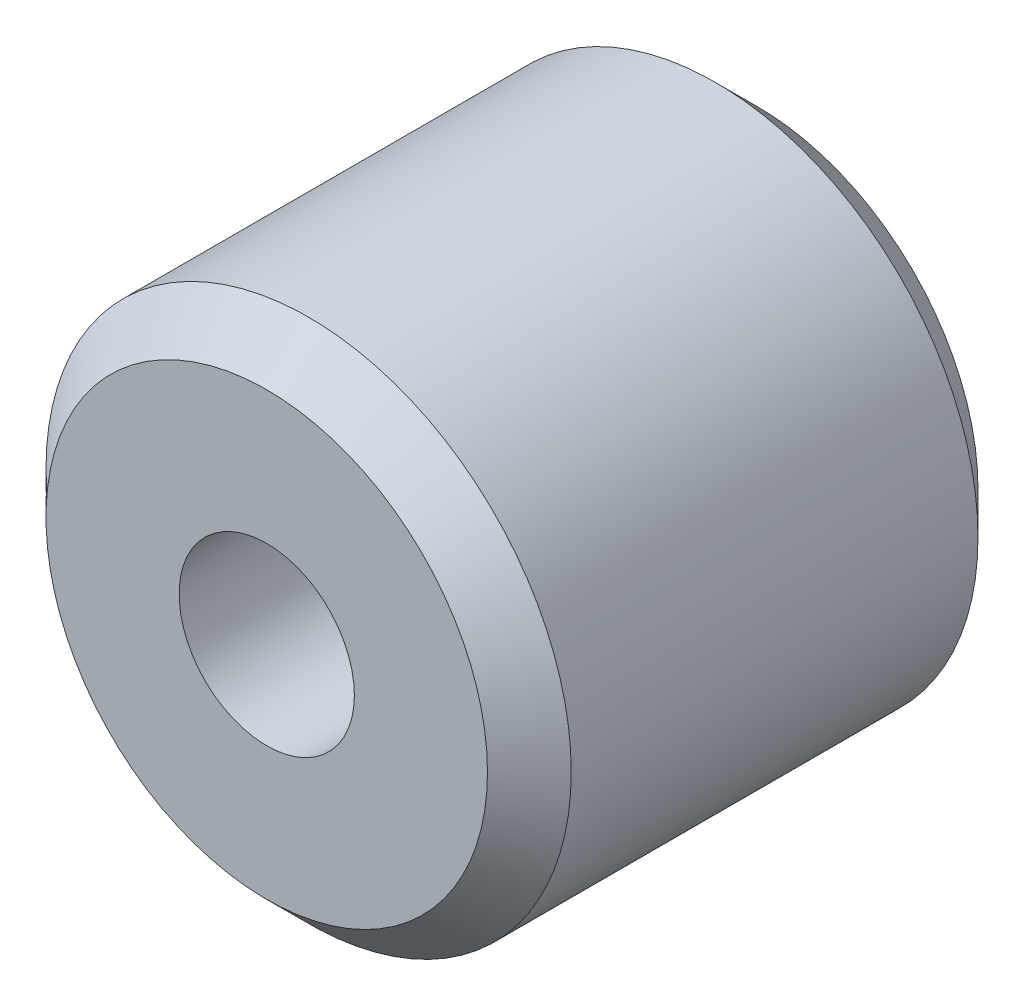
SolidWorks part; units mm, degrees
material "Alloy Steel"
ref_plane "Front Plane" through (0, 0, 0) normal (0, 0, 1) x (1, 0, 0)
ref_plane "Top Plane" through (0, 0, 0) normal (0, 1, 0) x (1, 0, 0)
ref_plane "Right Plane" through (0, 0, 0) normal (1, 0, 0) x (0, 0, -1)
sketch "Sketch1" plane through (0, 0, 0) normal (0, 0, 1) x (1, 0, 0)
  circle A0 centre (0, 0) radius 1.59
  circle A1 centre (0, 0) radius 4.765
  dimension "D1" = 9.53
  dimension "D2" = 3.18
extrude "Boss-Extrude1" add sketch "Sketch1" along normal mid plane 8.9
chamfer "Chamfer1" distance 0.76 2 edges at (4.765, 0, -4.45) (4.765, 0, 4.45)
